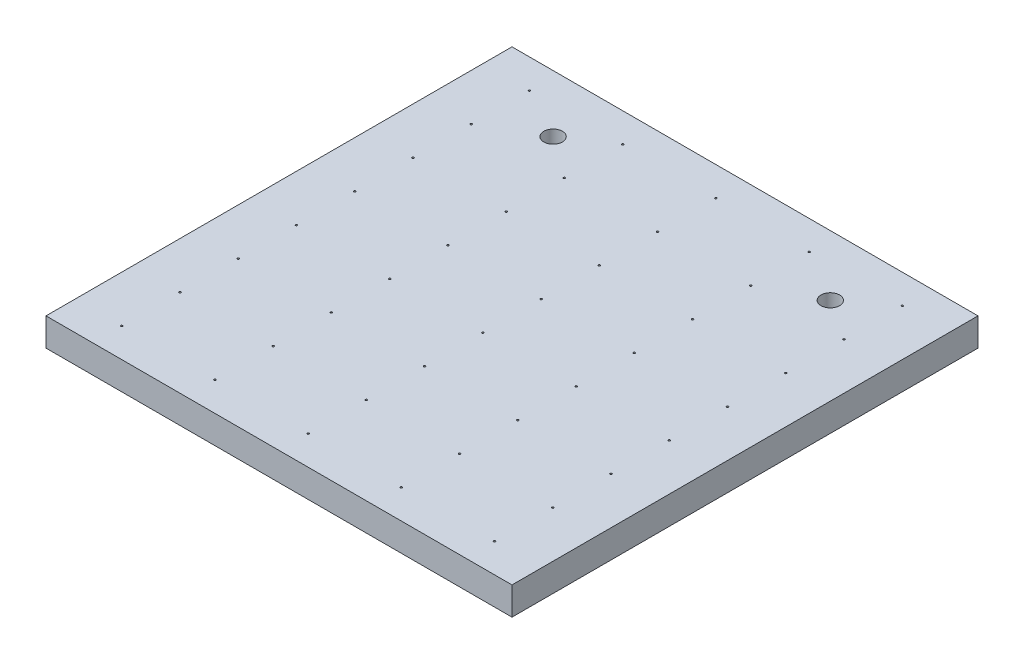
SolidWorks part; units mm, degrees
ref_plane "前视基准面" through (0, 0, 0) normal (0, 0, 1) x (1, 0, 0)
ref_plane "上视基准面" through (0, 0, 0) normal (0, 1, 0) x (1, 0, 0)
ref_plane "右视基准面" through (0, 0, 0) normal (1, 0, 0) x (0, 0, -1)
sketch "草图1" plane through (0, 0, 0) normal (0, 1, 0) x (1, 0, 0)
  line L1 (25, -25) -> (-25, -25)
  line L2 (25, -25) -> (25, 25)
  line L3 (25, 25) -> (-25, 25)
  line L4 (-25, -25) -> (-25, 25)
  line L5 (25, -25) -> (-25, 25) construction
  line L6 (25, 25) -> (-25, -25) construction
  point P0 (0, 0)
  dimension "D1" = 50
  dimension "D2" = 50
extrude "凸台-拉伸1" add sketch "草图1" along normal blind 3
sketch "草图2" plane through (0, 3, 0) normal (0, 1, 0) x (1, 0, 0)
  line L0 (-25, 25) -> (-25, -25) construction
  line L1 (25, 25) -> (-25, 25) construction
  circle A0 centre (-20, 21.875) radius 0.1
  dimension "D1" = 5
  dimension "D2" = 3.125
extrude "切除-拉伸5" cut sketch "草图2" against normal blind 0.6
pattern_linear "阵列(线性)6" count 5 spacing 10 along (1, 0, 0) of "切除-拉伸5"
sketch "草图6" plane through (0, 3, 0) normal (0, 1, 0) x (1, 0, 0)
  line L0 (-25, 25) -> (-25, -25) construction
  circle A0 centre (-20, 15.625) radius 0.1
  circle A1 centre (-20, 21.875) radius 0.1 construction
  point P6 (0, 0)
  dimension "D1" = 5
  dimension "D2" = 6.25
extrude "切除-拉伸6" cut sketch "草图6" against normal blind 0.8
pattern_linear "阵列(线性)7" count 5 spacing 10 along (1, 0, 0) of "切除-拉伸6"
sketch "草图7" plane through (0, 3, 0) normal (0, 1, 0) x (1, 0, 0)
  line L0 (-25, 25) -> (-25, -25) construction
  circle A0 centre (-20, 9.375) radius 0.1
  circle A1 centre (-20, 15.625) radius 0.1 construction
  dimension "D1" = 5
  dimension "D2" = 6.25
extrude "切除-拉伸7" cut sketch "草图7" against normal blind 1
pattern_linear "阵列(线性)8" count 5 spacing 10 along (1, 0, 0) of "切除-拉伸7"
sketch "草图8" plane through (0, 3, 0) normal (0, 1, 0) x (1, 0, 0)
  line L0 (-25, 25) -> (-25, -25) construction
  circle A0 centre (-20, 3.125) radius 0.1
  circle A2 centre (-20, 9.375) radius 0.1 construction
  point P4 (0, 0)
  point P6 (-20.1472, 6.8865)
  dimension "D1" = 5
  dimension "D2" = 6.25
extrude "切除-拉伸8" cut sketch "草图8" against normal blind 1.2
pattern_linear "阵列(线性)9" count 5 spacing 10 along (1, 0, 0) of "切除-拉伸8"
sketch "草图9" plane through (0, 3, 0) normal (0, 1, 0) x (1, 0, 0)
  line L0 (-25, 25) -> (-25, -25) construction
  circle A0 centre (-20, -3.125) radius 0.1
  circle A1 centre (-20, 3.125) radius 0.1 construction
  dimension "D1" = 5
  dimension "D2" = 6.25
extrude "切除-拉伸9" cut sketch "草图9" against normal blind 1.4
pattern_linear "阵列(线性)10" count 5 spacing 10 along (1, 0, 0) of "切除-拉伸9"
sketch "草图10" plane through (0, 3, 0) normal (0, 1, 0) x (1, 0, 0)
  line L0 (-25, 25) -> (-25, -25) construction
  circle A0 centre (-20, -9.375) radius 0.1
  circle A1 centre (-20, -3.125) radius 0.1 construction
  dimension "D1" = 5
  dimension "D2" = 6.25
extrude "切除-拉伸10" cut sketch "草图10" against normal blind 1.6
pattern_linear "阵列(线性)11" count 5 spacing 10 along (1, 0, 0) of "切除-拉伸10"
sketch "草图11" plane through (0, 3, 0) normal (0, 1, 0) x (1, 0, 0)
  line L0 (-25, 25) -> (-25, -25) construction
  circle A0 centre (-20, -15.625) radius 0.1
  circle A1 centre (-20, -9.375) radius 0.1 construction
  dimension "D1" = 5
  dimension "D2" = 6.25
extrude "切除-拉伸11" cut sketch "草图11" against normal blind 1.8
pattern_linear "阵列(线性)12" count 5 spacing 10 along (1, 0, 0) of "切除-拉伸11"
sketch "草图12" plane through (0, 3, 0) normal (0, 1, 0) x (1, 0, 0)
  line L0 (-25, 25) -> (-25, -25) construction
  circle A0 centre (-20, -21.875) radius 0.1
  circle A1 centre (-20, -15.625) radius 0.1 construction
  dimension "D1" = 5
  dimension "D2" = 6.25
extrude "切除-拉伸12" cut sketch "草图12" against normal blind 2
pattern_linear "阵列(线性)13" count 5 spacing 10 along (1, 0, 0) of "切除-拉伸12"
sketch "草图13" plane through (0, 3, 0) normal (0, 1, 0) x (1, 0, 0)
  circle A0 centre (-14.4508, 18.8602) radius 1
extrude "切除-拉伸13" cut sketch "草图13" against normal through all
sketch "草图14" plane through (0, 3, 0) normal (0, 1, 0) x (1, 0, 0)
  circle A0 centre (15.6322, 18.5207) radius 1
extrude "切除-拉伸14" cut sketch "草图14" against normal through all
